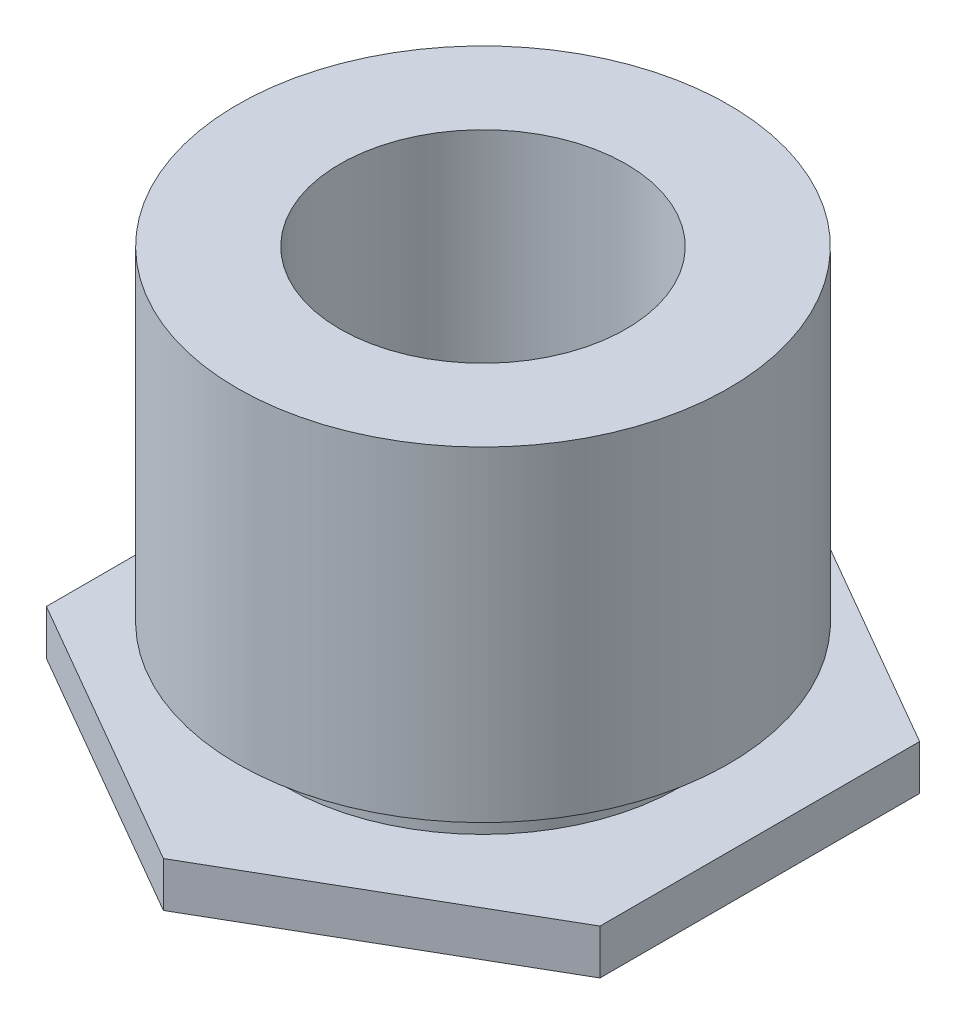
SolidWorks part; units mm, degrees
other "Детальный элемент1"
other "Детальный элемент2"
material "A2"
ref_plane "Спереди" through (0, 0, 0) normal (0, 0, 1) x (1, 0, 0)
ref_plane "Сверху" through (0, 0, 0) normal (0, 1, 0) x (1, 0, 0)
ref_plane "Справа" through (0, 0, 0) normal (1, 0, 0) x (0, 0, -1)
sketch "Эскиз1" plane through (0, 0, 0) normal (0, 1, 0) x (1, 0, 0)
  line L1 (0, -4.6188) -> (4, -2.3094)
  line L2 (4, -2.3094) -> (4, 2.3094)
  line L3 (4, 2.3094) -> (0, 4.6188)
  line L4 (0, 4.6188) -> (-4, 2.3094)
  line L5 (-4, 2.3094) -> (-4, -2.3094)
  line L6 (-4, -2.3094) -> (0, -4.6188)
  circle A0 centre (0, 0) radius 4 construction
  dimension "Размер шестигранника шляпки" = 8
extrude "Бобышка-Вытянуть1" add sketch "Эскиз1" along normal blind 0.65
sketch "Эскиз6" plane through (0, 0, 0) normal (0, 0, 1) x (1, 0, 0)
  line L0 (3.55, 6) -> (3.55, 1.3)
  line L1 (3.55, 1.3) -> (2.84, 1.3)
  line L2 (2.84, 1.3) -> (2.84, 0.65)
  line L3 (0, 0.65) -> (4, 0.65) construction
  line L4 (2.84, 0.65) -> (0, 0.65)
  line L5 (0, 0.65) -> (0, 2.8)
  line L6 (0, 2.8) -> (2.067, 2.8)
  line L7 (2.067, 2.8) -> (2.067, 6)
  line L8 (2.067, 6) -> (3.55, 6)
  line L9 (0, 2.8) -> (0, 0) construction
  line L10 (4, 0.65) -> (4, 0) construction
  line L11 (0, 0) -> (4, 0) construction
revolve "Повернуть1" add sketch "Эскиз6" angle 360 about L9
cosmetic thread "Условное изображение резьбы1"
equation "\"D1@Эскиз6\"=\"Внешний диаметр@Эскиз6\" * 0.8"
